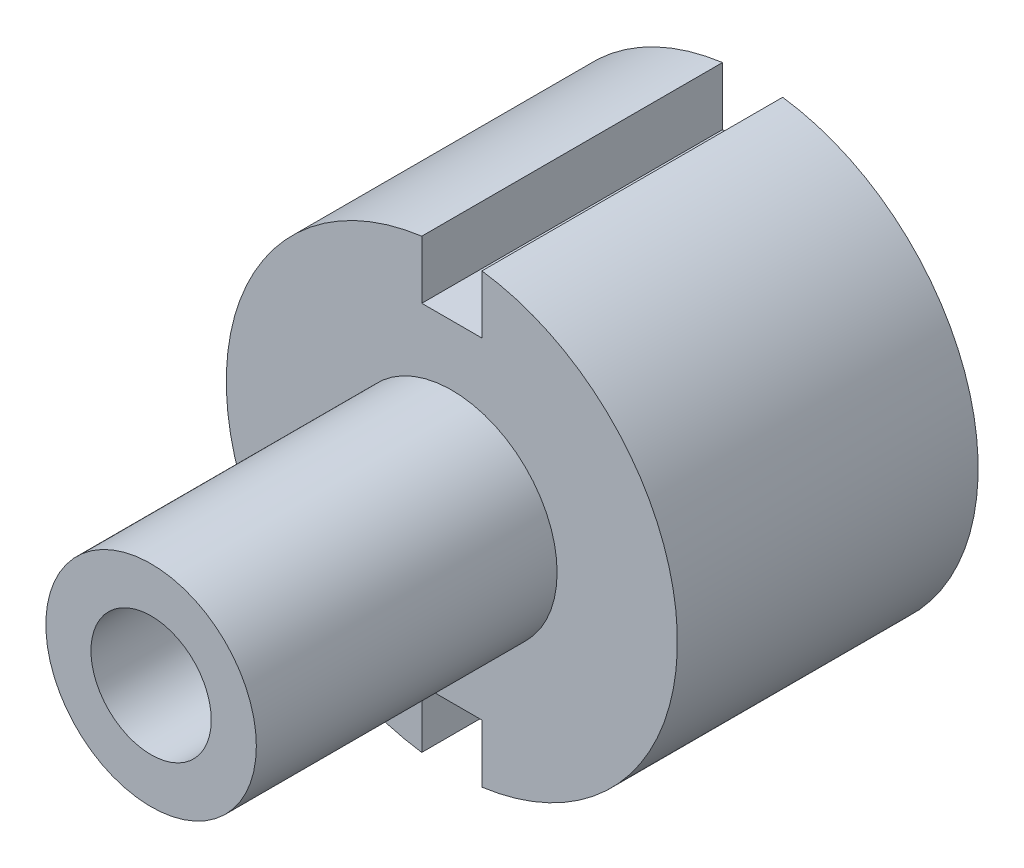
SolidWorks part; units mm, degrees
ref_plane "Front" through (0, 0, 0) normal (0, 0, 1) x (1, 0, 0)
ref_plane "Top" through (0, 0, 0) normal (0, 1, 0) x (1, 0, 0)
ref_plane "Right" through (0, 0, 0) normal (1, 0, 0) x (0, 0, -1)
sketch "Эскиз1" plane through (0, 0, 0) normal (0, 0, 1) x (1, 0, 0)
  circle A2 centre (0, 0) radius 7.5
  dimension "D3" = 15
extrude "Бобышка-Вытянуть1" add sketch "Эскиз1" along normal mid plane 10
sketch "Эскиз6" plane through (0, 0, 5) normal (0, 0, 1) x (1, 0, 0)
  circle A0 centre (0, 0) radius 3.5
  dimension "D1" = 7
extrude "Бобышка-Вытянуть2" add sketch "Эскиз6" along normal blind 10
sketch "Эскиз7" plane through (0, 0, 15) normal (0, 0, 1) x (1, 0, 0)
  circle A0 centre (0, 0) radius 2
  dimension "D1" = 4
extrude "Вырез-Вытянуть1" cut sketch "Эскиз7" against normal blind 3
sketch "Эскиз8" plane through (0, 0, 12) normal (0, 0, 1) x (1, 0, 0)
  line L0 (-1.2639, 1.55) -> (1.2639, 1.55)
  circle A0 centre (0, 0) radius 2 construction
  circle M2 centre (0, 0) radius 2
  dimension "D1" = 1.55
extrude "Вырез-Вытянуть2" cut sketch "Эскиз8" against normal blind 7 and the other way through all contours L0 M2
sketch "Эскиз10" plane through (0, 0, 5) normal (0, 0, 1) x (1, 0, 0)
  line L0 (0, 7.5) -> (0, -7.5) construction
  line L1 (-7.5, 0) -> (7.5, 0) construction
  line L3 (-1, 7.5) -> (1, 7.5)
  line L4 (-1, 7.5) -> (-1, 5.5)
  line L5 (-1, 5.5) -> (1, 5.5)
  line L6 (1, 7.5) -> (1, 5.5)
  line L7 (1, -7.5) -> (-1, -7.5)
  line L8 (1, -7.5) -> (1, -5.5)
  line L9 (1, -5.5) -> (-1, -5.5)
  line L10 (-1, -7.5) -> (-1, -5.5)
  circle A0 centre (0, 0) radius 7.5 construction
  dimension "D1" = 2
  dimension "D2" = 2
extrude "Вырез-Вытянуть4" cut sketch "Эскиз10" against normal blind 10
